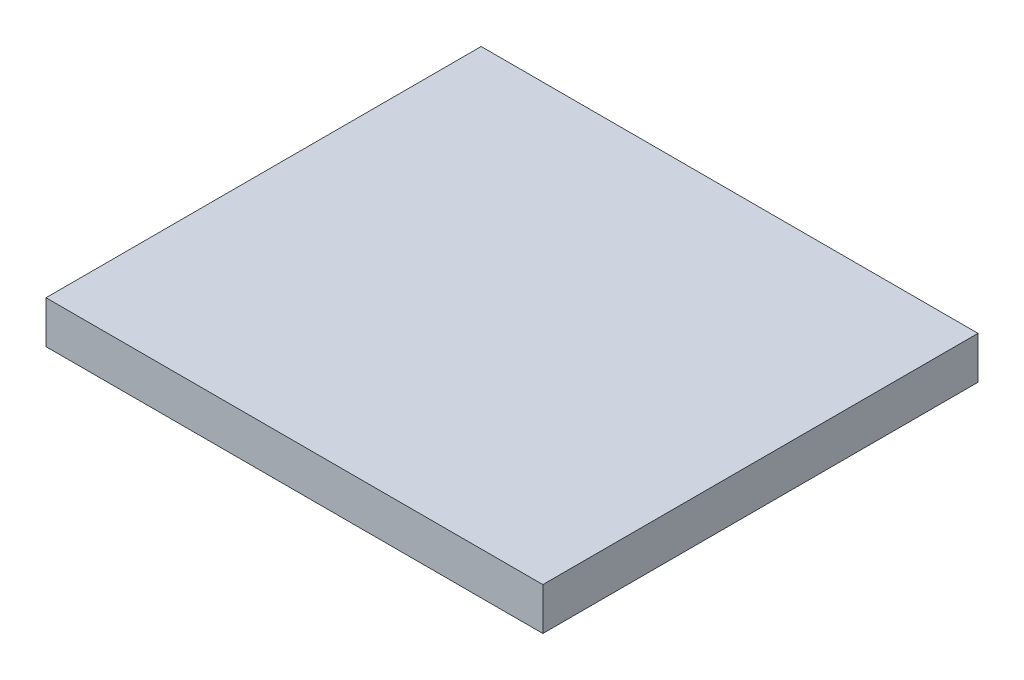
SolidWorks part; units mm, degrees
ref_plane "Front Plane" through (0, 0, 0) normal (0, 0, 1) x (1, 0, 0)
ref_plane "Top Plane" through (0, 0, 0) normal (0, 1, 0) x (1, 0, 0)
ref_plane "Right Plane" through (0, 0, 0) normal (1, 0, 0) x (0, 0, -1)
sketch "Sketch1" plane through (0, 0, 0) normal (0, 1, 0) x (1, 0, 0)
  line L1 (-29.307, -25.6689) -> (29.307, -25.6689)
  line L2 (-29.307, -25.6689) -> (-29.307, 25.6689)
  line L3 (-29.307, 25.6689) -> (29.307, 25.6689)
  line L4 (29.307, -25.6689) -> (29.307, 25.6689)
  line L5 (-29.307, -25.6689) -> (29.307, 25.6689) construction
  line L6 (-29.307, 25.6689) -> (29.307, -25.6689) construction
  point P0 (0, 0)
extrude "Boss-Extrude1" add sketch "Sketch1" along normal blind 5
